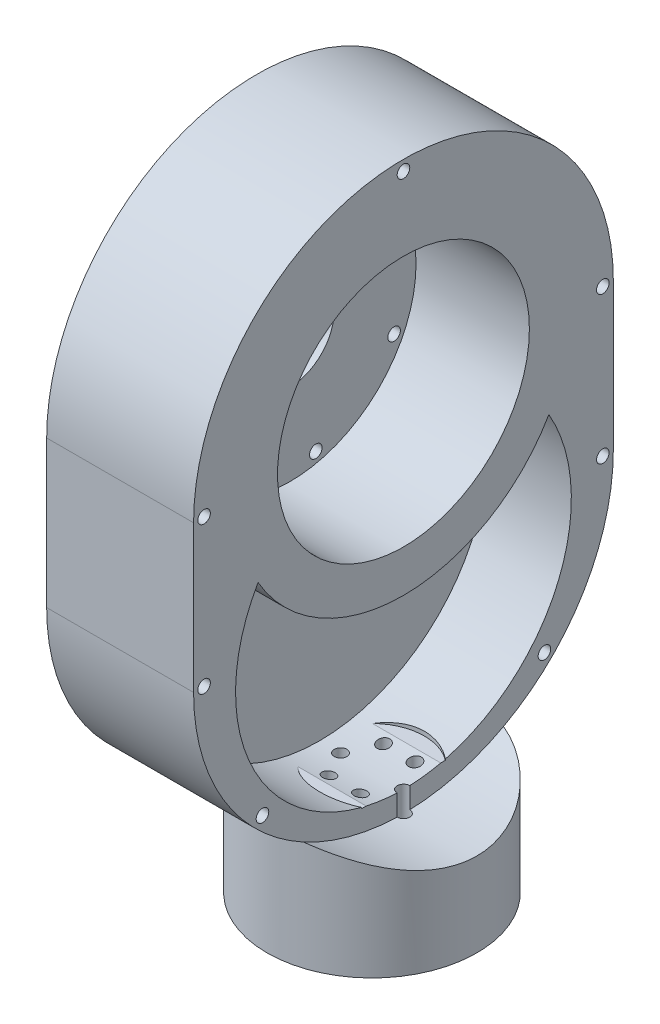
SolidWorks part; units mm, degrees
material "ABS"
ref_plane "Alzado" through (0, 0, 0) normal (0, 0, 1) x (1, 0, 0)
ref_plane "Planta" through (0, 0, 0) normal (0, 1, 0) x (1, 0, 0)
ref_plane "Vista lateral" through (0, 0, 0) normal (1, 0, 0) x (0, 0, -1)
sketch "Croquis3" plane through (0, 0, 0) normal (1, 0, 0) x (0, 0, -1)
  line L0 (-50, 105) -> (-50, 70)
  line L1 (50, 70) -> (50, 105)
  arc A0 (50, 105) -> (-50, 105) centre (0, 105) ccw
  arc A1 (-50, 70) -> (50, 70) centre (0, 70) ccw
  dimension "D1" = 100
  dimension "D3" = 35
  dimension "D4" = 70
extrude "Saliente-Extruir3" add sketch "Croquis3" along normal mid plane 55
sketch "Croquis2" plane through (0, 0, 0) normal (0, 1, 0) x (1, 0, 0)
  circle A0 centre (0, 0) radius 25
  dimension "D1" = 50
extrude "Saliente-Extruir4" add sketch "Croquis2" along normal up to next
sketch "Croquis5" plane through (-27.5, 0, 0) normal (-1, 0, 0) x (0, 0, 1)
  circle A0 centre (0, 105) radius 45
  circle A1 centre (0, 105) radius 32.5
  dimension "D1" = 90
  dimension "D2" = 65
extrude "Cortar-Extruir2" cut sketch "Croquis5" against normal blind 1.5
sketch "Croquis6" plane through (-27.5, 0, 0) normal (-1, 0, 0) x (0, 0, 1)
  circle A0 centre (0, 105) radius 10.5
  dimension "D1" = 21
extrude "Cortar-Extruir3" cut sketch "Croquis6" against normal through all
sketch "Croquis7" plane through (27.5, 0, 0) normal (1, 0, 0) x (0, 0, -1)
  line L2 (-50, 105) -> (-50, 70)
  line L3 (50, 70) -> (50, 105)
  line L4 (-50, 105) -> (-50, 70)
  line L5 (50, 70) -> (50, 105)
  arc A2 (50, 105) -> (-50, 105) centre (0, 105) ccw
  arc A3 (-50, 70) -> (50, 70) centre (0, 70) ccw
  arc A4 (50, 105) -> (-50, 105) centre (0, 105) ccw
  arc A5 (-50, 70) -> (50, 70) centre (0, 70) ccw
  dimension "D1" = 0
extrude "Cortar-Extruir4" cut sketch "Croquis7" against normal blind 20
sketch "Croquis8" plane through (7.5, 0, 0) normal (1, 0, 0) x (0, 0, -1)
  circle A0 centre (0, 105) radius 30
  dimension "D1" = 60
extrude "Cortar-Extruir5" cut sketch "Croquis8" against normal blind 27
sketch "Croquis9" plane through (0, 0, 0) normal (0, -1, 0) x (1, 0, 0)
  circle A6 centre (0, 0) radius 7.5 construction
  circle A7 centre (7.5, 0) radius 1.5
  circle A8 centre (3.75, -6.4952) radius 1.5
  circle A9 centre (-3.75, -6.4952) radius 1.5
  circle A10 centre (-7.5, 0) radius 1.5
  circle A11 centre (-3.75, 6.4952) radius 1.5
  circle A12 centre (3.75, 6.4952) radius 1.5
  point P17 (0, 0)
  dimension "D2" = 3
  dimension "D1" = 15
extrude "Cortar-Extruir7" cut sketch "Croquis9" against normal blind 30
ref_plane "Plano1" through (0, 26, 0) normal (0, 1, 0) x (1, 0, 0)
sketch "Croquis10" plane through (0, 26, 0) normal (0, 1, 0) x (1, 0, 0)
  circle A0 centre (0, 0) radius 12.5
  dimension "D1" = 25
extrude "Cortar-Extruir8" cut sketch "Croquis10" along normal blind 5
sketch "Croquis11" plane through (-27.5, 0, 0) normal (-1, 0, 0) x (0, 0, 1)
  circle A0 centre (0, 105) radius 27.5 construction
  circle A1 centre (27.5, 105) radius 1.5
  circle A2 centre (17.146, 83.4996) radius 1.5
  circle A3 centre (-6.1193, 78.1895) radius 1.5
  circle A4 centre (-24.7766, 93.0682) radius 1.5
  circle A5 centre (-24.7766, 116.9318) radius 1.5
  circle A6 centre (-6.1193, 131.8105) radius 1.5
  circle A7 centre (17.146, 126.5004) radius 1.5
  point P20 (0, 105)
  dimension "D1" = 3
  dimension "D2" = 7
extrude "Cortar-Extruir9" cut sketch "Croquis11" against normal through all
sketch "Croquis12" plane through (7.5, 0, 0) normal (1, 0, 0) x (0, 0, -1)
  line L0 (-1.5, 0) -> (1.5, 0) construction
  arc A0 (-34.641, 85) -> (34.641, 85) centre (0, 65) ccw
  arc A1 (-34.641, 85) -> (34.641, 85) centre (0, 105) ccw
  dimension "D1" = 80
  dimension "D3" = 80
  dimension "D2" = 65
extrude "Cortar-Extruir10" cut sketch "Croquis12" against normal blind 20
sketch "Croquis13" plane through (7.5, 0, 0) normal (1, 0, 0) x (0, 0, -1)
  circle A0 centre (0, 152.5) radius 1.5
  circle A1 centre (0, 105) radius 47.5 construction
  circle A2 centre (47.5, 105) radius 1.5
  circle A3 centre (0, 57.5) radius 1.5 construction
  circle A4 centre (-47.5, 105) radius 1.5
  circle A5 centre (0, 70) radius 47.5 construction
  circle A6 centre (-47.5, 70) radius 1.5
  circle A7 centre (-33.5876, 103.5876) radius 1.5 construction
  circle A8 centre (0, 117.5) radius 1.5 construction
  circle A9 centre (33.5876, 103.5876) radius 1.5 construction
  circle A10 centre (47.5, 70) radius 1.5
  circle A11 centre (33.5876, 36.4124) radius 1.5
  circle A12 centre (0, 22.5) radius 1.5 construction
  circle A13 centre (-33.5876, 36.4124) radius 1.5
  point P14 (0, 105)
  point P33 (0, 70)
  dimension "D1" = 95
  dimension "D3" = 3
  dimension "D4" = 95
  dimension "D5" = 3
  dimension "D2" = 4
  dimension "D6" = 8
extrude "Cortar-Extruir11" cut sketch "Croquis13" against normal through all
sketch "Croquis14" plane through (0, 0, 0) normal (0, -1, 0) x (1, 0, 0)
  circle A0 centre (0, 0) radius 17.5
  circle A1 centre (0, 0) radius 10
  dimension "D1" = 35
  dimension "D2" = 20
extrude "Cortar-Extruir12" cut sketch "Croquis14" against normal blind 2
sketch "Croquis15" plane through (-27.5, 0, 0) normal (-1, 0, 0) x (0, 0, 1)
  circle A0 centre (0, 105) radius 13.5
  circle A1 centre (0, 105) radius 10
  dimension "D1" = 27
  dimension "D2" = 20
extrude "Cortar-Extruir13" cut sketch "Croquis15" against normal blind 4
